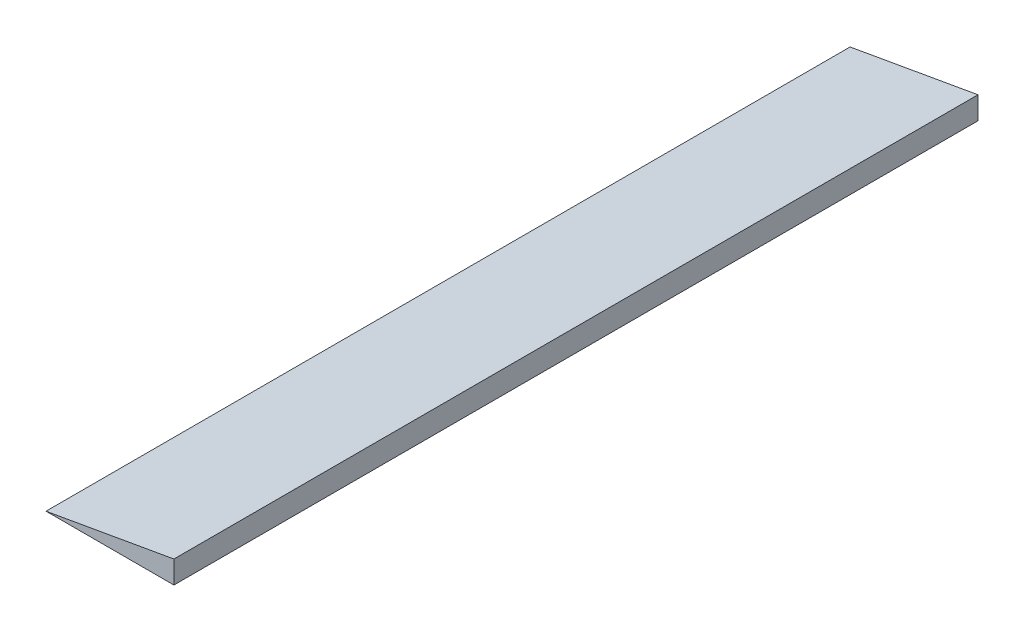
SolidWorks part; units mm, degrees
ref_plane "Front Plane" through (0, 0, 0) normal (0, 0, 1) x (1, 0, 0)
ref_plane "Top Plane" through (0, 0, 0) normal (0, 1, 0) x (1, 0, 0)
ref_plane "Right Plane" through (0, 0, 0) normal (1, 0, 0) x (0, 0, -1)
sketch "Sketch1" plane through (0, 0, 0) normal (0, 0, 1) x (1, 0, 0)
  line L0 (0, 0) -> (88.9, 0)
  line L1 (88.9, 0) -> (88.9, 15.6755)
  line L2 (88.9, 15.6755) -> (0, 0)
  dimension "D1" = 10
  dimension "D2" = 88.9
extrude "Boss-Extrude1" add sketch "Sketch1" along normal mid plane 558.8
